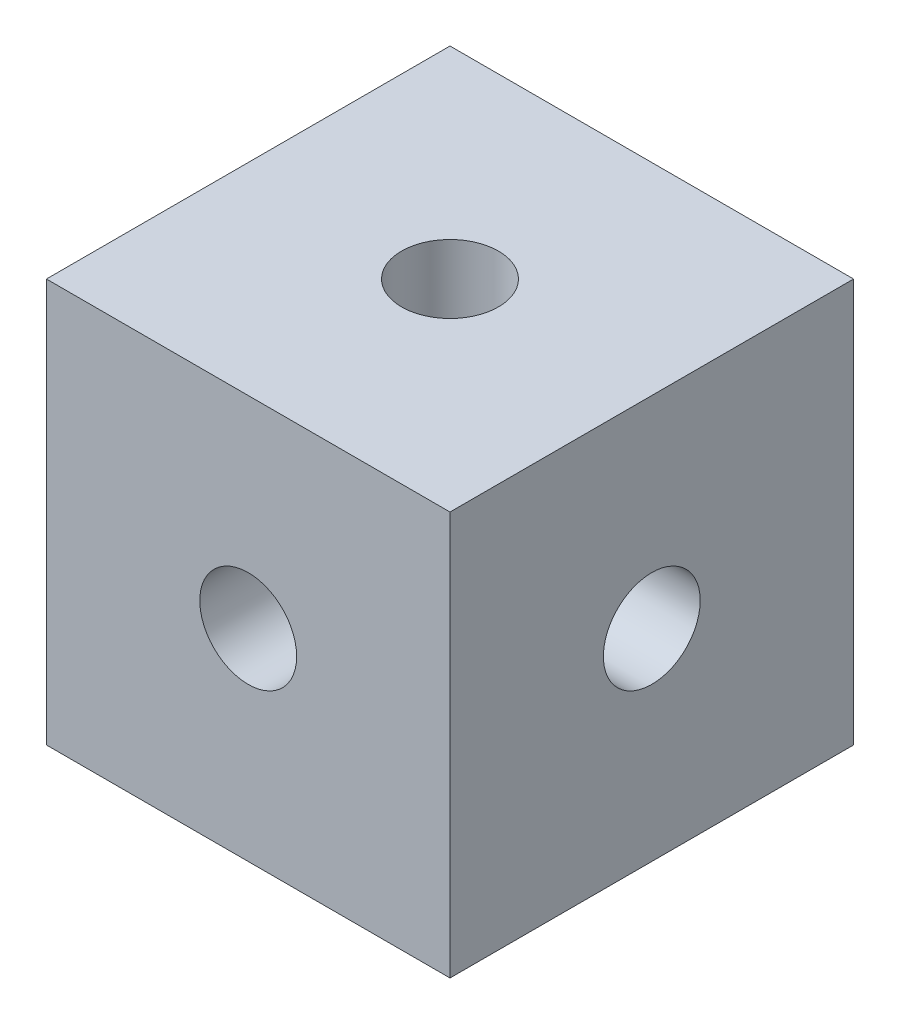
SolidWorks part; units mm, degrees
material "6061 合金"
ref_plane "前视基准面" through (0, 0, 0) normal (0, 0, 1) x (1, 0, 0)
ref_plane "上视基准面" through (0, 0, 0) normal (0, 1, 0) x (1, 0, 0)
ref_plane "右视基准面" through (0, 0, 0) normal (1, 0, 0) x (0, 0, -1)
sketch "草图1" plane through (0, 0, 0) normal (0, 0, 1) x (1, 0, 0)
  line L0 (0, 0) -> (10, 0)
  line L1 (10, 0) -> (10, 10)
  line L2 (10, 10) -> (0, 10)
  line L3 (0, 10) -> (0, 0)
  line L4 (5, 5) -> (5, 0) construction
  line L5 (5, 5) -> (0, 5) construction
  circle A0 centre (5, 5) radius 1.2
  point P5 (5, 5)
  dimension "D3" = 2.4
  dimension "D1" = 10
  dimension "D2" = 10
extrude "凸台-拉伸1" add sketch "草图1" along normal blind 10
sketch "草图2" plane through (0, 10, 0) normal (0, 1, 0) x (1, 0, 0)
  line L0 (5, 0) -> (5, -5) construction
  line L1 (10, 0) -> (0, 0) construction
  line L2 (5, -5) -> (10, -5) construction
  line L3 (10, -10) -> (10, 0) construction
  circle A0 centre (5, -5) radius 1.2
  dimension "D1" = 2.4
extrude "切除-拉伸1" cut sketch "草图2" against normal through all
sketch "草图3" plane through (10, 0, 0) normal (1, 0, 0) x (0, 0, -1)
  line L0 (-5, 10) -> (-5, 5) construction
  line L1 (-10, 10) -> (0, 10) construction
  line L2 (-5, 5) -> (0, 5) construction
  line L3 (0, 0) -> (0, 10) construction
  circle A0 centre (-5, 5) radius 1.2
  dimension "D1" = 2.4
extrude "切除-拉伸2" cut sketch "草图3" against normal blind 10
cosmetic thread "装饰螺纹线3" parameters "D1"=4.1514, "D2"=3
